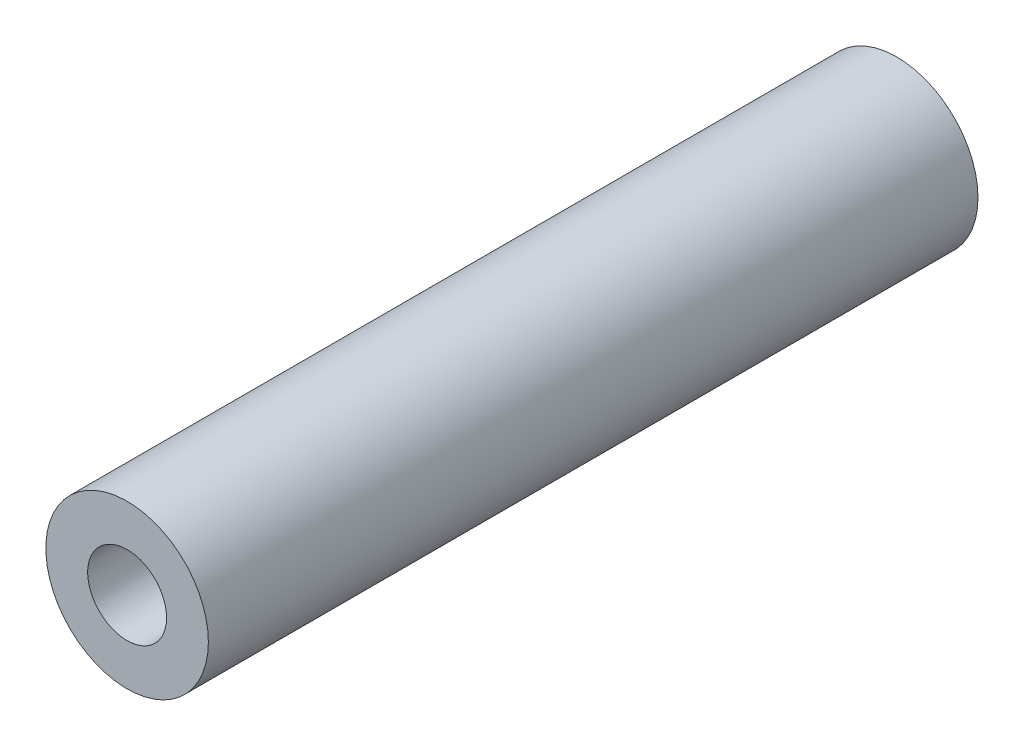
SolidWorks part; units mm, degrees
ref_plane "Front Plane" through (0, 0, 0) normal (0, 0, 1) x (1, 0, 0)
ref_plane "Top Plane" through (0, 0, 0) normal (0, 1, 0) x (1, 0, 0)
ref_plane "Right Plane" through (0, 0, 0) normal (1, 0, 0) x (0, 0, -1)
sketch "M3 clearance profile" plane through (0, 0, 0) normal (0, 0, 1) x (1, 0, 0)
  circle A0 centre (0, 0) radius 3.4
  circle A1 centre (0, 0) radius 1.65
extrude "M3 clearance" add sketch "M3 clearance profile" along normal blind 32.2
